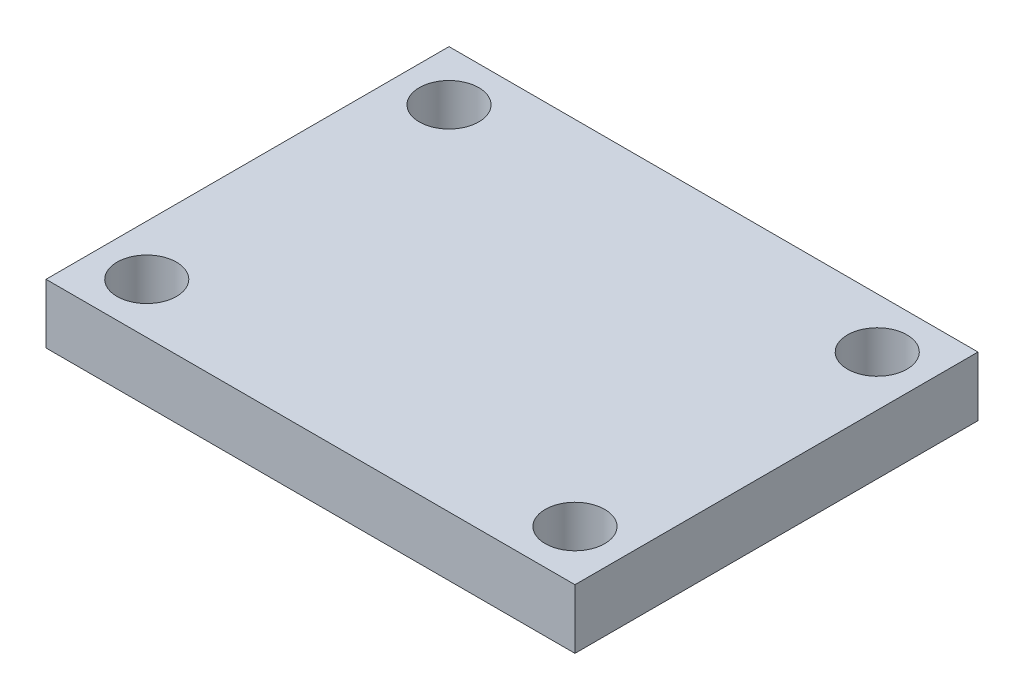
SolidWorks part; units mm, degrees
ref_plane "Alzado" through (0, 0, 0) normal (0, 0, 1) x (1, 0, 0)
ref_plane "Planta" through (0, 0, 0) normal (0, 1, 0) x (1, 0, 0)
ref_plane "Vista lateral" through (0, 0, 0) normal (1, 0, 0) x (0, 0, -1)
sketch "Croquis1" plane through (0, 0, 0) normal (0, 1, 0) x (1, 0, 0)
  line L1 (0, 0) -> (26.67, 0)
  line L2 (0, 0) -> (0, 20.32)
  line L3 (0, 20.32) -> (26.67, 20.32)
  line L4 (26.67, 0) -> (26.67, 20.32)
  dimension "D1" = 20.32
  dimension "D2" = 26.67
extrude "Saliente-Extruir1" add sketch "Croquis1" along normal blind 3 contours L2 L1 L4 L3
sketch "Croquis2" plane through (0, 3, 0) normal (0, 1, 0) x (1, 0, 0)
  line L0 (13.335, 0) -> (13.335, 20.32) construction
  line L1 (0, 0) -> (26.67, 0) construction
  line L2 (0, 20.32) -> (26.67, 20.32) construction
  line L3 (0, 0) -> (0, 20.32) construction
  line L4 (26.67, 0) -> (26.67, 20.32) construction
  circle A0 centre (24.13, 2.54) radius 1.5
  circle A1 centre (2.54, 2.54) radius 1.5
  circle A2 centre (2.54, 17.78) radius 1.5
  circle A3 centre (24.13, 17.78) radius 1.5
  dimension "D1" = 2.54
  dimension "D2" = 2.54
  dimension "D3" = 2.54
  dimension "D4" = 2.54
  dimension "D5" = 2.54
  dimension "D6" = 2.54
  dimension "D7" = 2.54
  dimension "D8" = 2.54
  dimension "D9" = 3
  dimension "D10" = 3
  dimension "D11" = 3
  dimension "D12" = 3
extrude "Cortar-Extruir1" cut sketch "Croquis2" against normal through all
